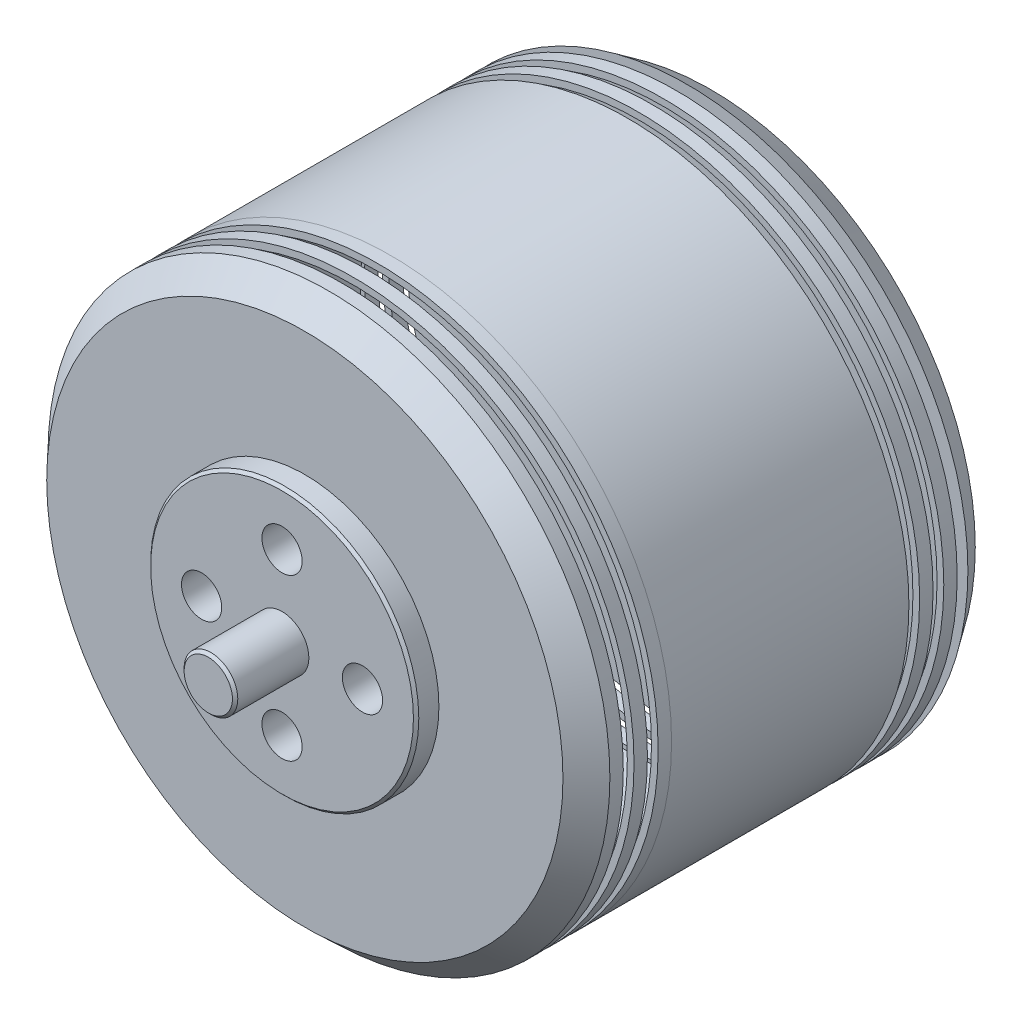
SolidWorks part; units mm, degrees
ref_plane "前视基准面" through (0, 0, 0) normal (0, 0, 1) x (1, 0, 0)
ref_plane "上视基准面" through (0, 0, 0) normal (0, 1, 0) x (1, 0, 0)
ref_plane "右视基准面" through (0, 0, 0) normal (1, 0, 0) x (0, 0, -1)
sketch "草图1" plane through (0, 0, 0) normal (0, 0, 1) x (1, 0, 0)
  circle A0 centre (0, 0) radius 19.7
  dimension "D1" = 39.4
ref_plane "基准面1" through (0, 0, 1.8) normal (0, 0, 1) x (1, 0, 0)
sketch "草图2" plane through (0, 0, 1.8) normal (0, 0, 1) x (1, 0, 0)
  circle A0 centre (0, 0) radius 20.95
  dimension "D1" = 41.9
loft "放样1" add profiles "草图2", "草图1"
ref_plane "基准面2" through (0, 0, 2.6) normal (0, 0, 1) x (1, 0, 0)
sketch "草图3" plane through (0, 0, 2.6) normal (0, 0, 1) x (1, 0, 0)
  circle A0 centre (0, 0) radius 20.95 construction
  circle A1 centre (0, 0) radius 20.95
  circle A2 centre (0, 0) radius 20.45
  dimension "D1" = 0.5
extrude "凸台-拉伸1" add sketch "草图3" along normal blind 1 separate body
ref_plane "基准面3" through (0, 0, 4.4) normal (0, 0, 1) x (1, 0, 0)
sketch "草图4" plane through (0, 0, 4.4) normal (0, 0, 1) x (1, 0, 0)
  circle A1 centre (0, 0) radius 20.45 construction
  circle A4 centre (0, 0) radius 20.45
  circle A5 centre (0, 0) radius 20.95 construction
  circle A6 centre (0, 0) radius 20.95
extrude "凸台-拉伸2" add sketch "草图4" along normal blind 1 separate body
ref_plane "基准面4" through (0, 0, 6.2) normal (0, 0, 1) x (1, 0, 0)
sketch "草图5" plane through (0, 0, 6.2) normal (0, 0, 1) x (1, 0, 0)
  circle A0 centre (0, 0) radius 20.95 construction
  circle A1 centre (0, 0) radius 20.95
  circle A2 centre (0, 0) radius 19.95
  dimension "D1" = 1
extrude "凸台-拉伸3" add sketch "草图5" along normal blind 17.7 separate body
sketch "草图6" plane through (0, 0, 23.9) normal (0, 0, 1) x (1, 0, 0)
  circle A0 centre (0, 0) radius 20.95 construction
  circle A1 centre (0, 0) radius 20.95
  circle A2 centre (0, 0) radius 20.45 construction
  circle A3 centre (0, 0) radius 20.45
extrude "凸台-拉伸4" add sketch "草图6" along normal blind 1 separate body
ref_plane "基准面5" through (0, 0, 25.7) normal (0, 0, 1) x (1, 0, 0)
sketch "草图7" plane through (0, 0, 25.7) normal (0, 0, 1) x (1, 0, 0)
  circle A0 centre (0, 0) radius 20.95 construction
  circle A1 centre (0, 0) radius 20.95
  circle A2 centre (0, 0) radius 20.45 construction
  circle A3 centre (0, 0) radius 20.45
extrude "凸台-拉伸5" add sketch "草图7" along normal blind 1 separate body
ref_plane "基准面6" through (0, 0, 27.5) normal (0, 0, 1) x (1, 0, 0)
sketch "草图8" plane through (0, 0, 27.5) normal (0, 0, 1) x (1, 0, 0)
  circle A0 centre (0, 0) radius 20.95 construction
  circle A1 centre (0, 0) radius 20.95
  circle A2 centre (0, 0) radius 20.45 construction
  circle A3 centre (0, 0) radius 20.45
extrude "凸台-拉伸6" add sketch "草图8" along normal blind 1 separate body
ref_plane "基准面7" through (0, 0, 30.3) normal (0, 0, 1) x (1, 0, 0)
sketch "草图9" plane through (0, 0, 30.3) normal (0, 0, 1) x (1, 0, 0)
  circle A0 centre (0, 0) radius 19.25
  dimension "D1" = 38.5
sketch "草图10" plane through (0, 0, 28.5) normal (0, 0, 1) x (1, 0, 0)
  circle A0 centre (0, 0) radius 20.95 construction
  circle A1 centre (0, 0) radius 20.95
loft "放样2" add profiles "草图10", "草图9"
sketch "草图11" plane through (0, 0, 30.3) normal (0, 0, 1) x (1, 0, 0)
  circle A0 centre (0, 0) radius 10
  dimension "D1" = 20
extrude "凸台-拉伸7" add sketch "草图11" along normal blind 1.7
sketch "草图12" plane through (0, 0, 32) normal (0, 0, 1) x (1, 0, 0)
  circle A0 centre (0, 0) radius 2
  dimension "D1" = 4
extrude "凸台-拉伸8" add sketch "草图12" along normal blind 5.5
sketch "草图13" plane through (0, 0, 32) normal (0, 0, 1) x (1, 0, 0)
  line L0 (0, -6) -> (0, 6)
  line L1 (-6, 0) -> (6, 0)
  circle A0 centre (0, 0) radius 6
  point P6 (0, 0)
  point P9 (0, 0)
  dimension "D1" = 12
hole_wizard "大小mm 暗销孔1" positions "3D草图1" profile "草图14" hole size "Ø3.0" standard "GB"
sketch3d "3D草图1"
  point P0 (-6, 0, 32)
  point P3 (6, 0, 32)
  point P6 (0, -6, 32)
  point P9 (0, 6, 32)
sketch "草图14" plane through (-6, 0, 32) normal (1, 0, 0) x (0, -1, 0)
  line L0 (0, 0) -> (0, 5.9013)
  line L1 (0, 5.9013) -> (1.5, 5)
  line L2 (1.5, 5) -> (1.5, 0)
  line L5 (1.5, 0) -> (0, 0)
  line L10 (0, 5.9013) -> (-1.5, 5) construction
  line L11 (0, -6.35) -> (0, 107.95) construction
  dimension "孔直径" = 3
  dimension "孔深度" = 5
  dimension "导头角度" = 118
sketch "草图15" plane through (0, 0, 0) normal (0, 0, -1) x (-1, 0, 0)
  circle A0 centre (0, 0) radius 6.9
  dimension "D1" = 13.8
extrude "切除-拉伸1" cut sketch "草图15" against normal blind 5.5
sketch "草图16" plane through (0, 0, 1.8) normal (0, 0, 1) x (1, 0, 0)
  circle A0 centre (0, 0) radius 6.9 construction
  circle A1 centre (0, 0) radius 6.9
extrude "凸台-拉伸9" add sketch "草图16" against normal blind 1
sketch "草图17" plane through (0, 0, 0.8) normal (0, 0, -1) x (-1, 0, 0)
  circle A0 centre (0, 0) radius 4.5
  dimension "D1" = 9
extrude "凸台-拉伸10" add sketch "草图17" along normal up to surface (0.8 mm away) up to face at (-6.9, 0, 0)
sketch "草图18" plane through (0, 0, 0) normal (0, 0, -1) x (-1, 0, 0)
  circle A1 centre (0, 0) radius 4.5
  circle A2 centre (0, 0) radius 4.5
  dimension "D1" = 0
extrude "凸台-拉伸11" add sketch "草图18" along normal blind 2
sketch "草图19" plane through (0, 0, 0) normal (0, 0, -1) x (-1, 0, 0)
  line L0 (0, -12.5) -> (0, 12.5)
  line L1 (-12.5, 0) -> (12.5, 0)
  circle A0 centre (0, 0) radius 12.5
  point P6 (0, 0)
  point P9 (0, 0)
  dimension "D1" = 25
hole_wizard "大小mm 暗销孔2" positions "3D草图2" profile "草图20" hole size "Ø3.0" standard "GB"
sketch3d "3D草图2"
  point P0 (12.5, 0, 0)
  point P3 (0, 12.5, 0)
  point P6 (0, -12.5, 0)
  point P9 (-12.5, 0, 0)
sketch "草图20" plane through (12.5, 0, 0) normal (1, 0, 0) x (0, 1, 0)
  line L0 (0, 0) -> (0, 5.9013)
  line L1 (0, 5.9013) -> (1.5, 5)
  line L2 (1.5, 5) -> (1.5, 0)
  line L5 (1.5, 0) -> (0, 0)
  line L10 (0, 5.9013) -> (-1.5, 5) construction
  line L11 (0, -6.35) -> (0, 107.95) construction
  dimension "孔直径" = 3
  dimension "孔深度" = 5
  dimension "导头角度" = 118
chamfer "倒角1" distance 0.2 angle 45 2 edges at (2, 0, 37.5) (10, 0, 32)
